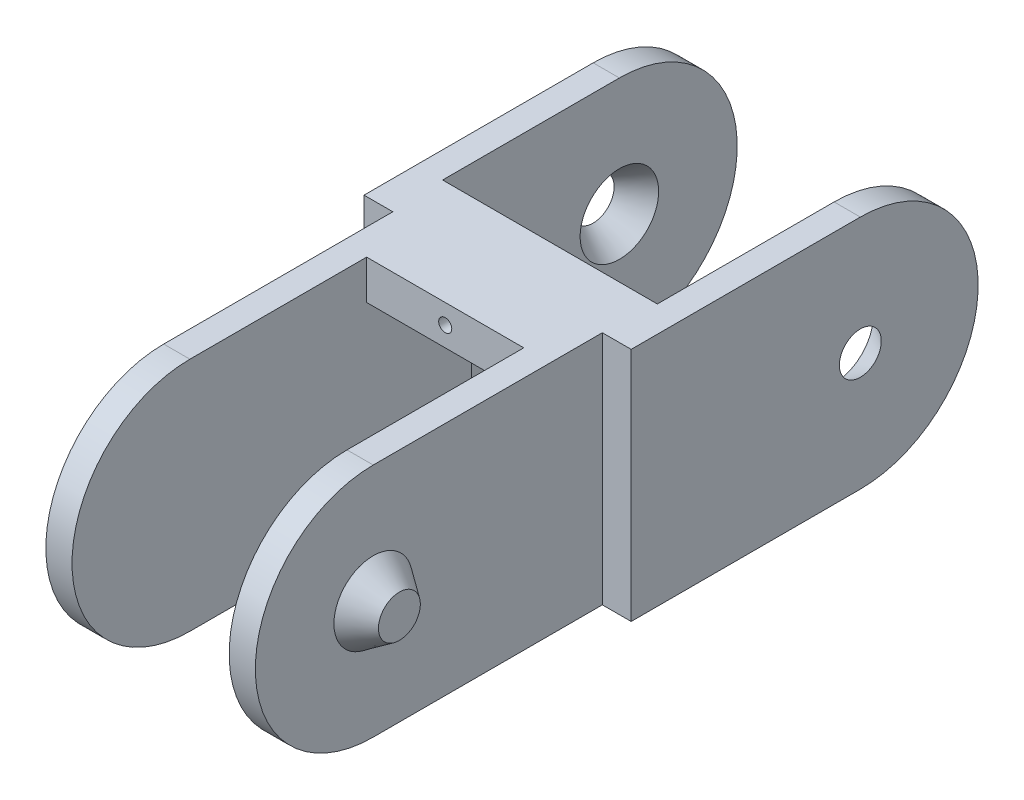
SolidWorks part; units mm, degrees
ref_plane "Front Plane" through (0, 0, 0) normal (0, 0, 1) x (1, 0, 0)
ref_plane "Top Plane" through (0, 0, 0) normal (0, 1, 0) x (1, 0, 0)
ref_plane "Right Plane" through (0, 0, 0) normal (1, 0, 0) x (0, 0, -1)
sketch "Sketch1" plane through (0, 0, 0) normal (0, 0, 1) x (1, 0, 0)
  line L1 (-6, -7) -> (6, -7)
  line L2 (-6, -7) -> (-6, 7)
  line L3 (-6, 7) -> (6, 7)
  line L4 (6, -7) -> (6, 7)
  line L5 (-6, -7) -> (6, 7) construction
  line L6 (-6, 7) -> (6, -7) construction
  point P0 (0, 0)
  dimension "D1" = 12
  dimension "D2" = 14
extrude "Extrude-Thin1" add sketch "Sketch1" along normal mid plane 8 thin
sketch "Sketch2" plane through (8, 0, 0) normal (1, 0, 0) x (0, 0, -1)
  line L0 (-4, 9) -> (4, 9) construction
  line L1 (0, 9) -> (-17.5, 9)
  line L2 (0, 9) -> (0, -9)
  line L3 (0, -9) -> (-17.5, -9)
  line L6 (-4, -9) -> (4, -9) construction
  line L7 (0, 55) -> (0, -55) construction
  line L8 (55, 0) -> (-55, 0) construction
  arc A0 (-17.5, 9) -> (-17.5, -9) centre (-17.5, 0) ccw
  dimension "D1" = 17.5
extrude "Boss-Extrude1" add sketch "Sketch2" against normal up to surface (2 mm away) up to face at (6, 0, 0)
sketch "Sketch3" plane through (8, 0, 0) normal (1, 0, 0) x (0, 0, -1)
  line L0 (55, 0) -> (-55, 0) construction
  circle A0 centre (-17.5, 0) radius 3
  arc A1 (-17.5, 9) -> (-17.5, -9) centre (-17.5, 0) ccw construction
  dimension "D1" = 6
extrude "Boss-Extrude2" add sketch "Sketch3" along normal blind 2 draft 35
sketch "Sketch4" plane through (8, 0, 0) normal (1, 0, 0) x (0, 0, -1)
  line L0 (0, 55) -> (0, -55) construction
  line L1 (0, 9) -> (17.5, 9)
  line L2 (0, 9) -> (0, -9)
  line L3 (0, -9) -> (17.5, -9)
  line L5 (-17.5, 9) -> (4, 9) construction
  line L6 (-17.5, -9) -> (4, -9) construction
  line L7 (55, 0) -> (-55, 0) construction
  arc A0 (17.5, 9) -> (17.5, -9) centre (17.5, 0) cw
  dimension "D1" = 17.5
extrude "Boss-Extrude3" add sketch "Sketch4" along normal blind 2.2
sketch "Sketch10" plane through (0, 9, 0) normal (0, 1, 0) x (1, 0, 0)
  line L1 (8, 4) -> (8.2, 4)
  line L2 (8, 4) -> (8, 29.5315)
  line L3 (8, 29.5315) -> (8.2, 29.5315)
  line L4 (8.2, 4) -> (8.2, 29.5315)
  dimension "D1" = 0.2
extrude "Cut-Extrude4" cut sketch "Sketch10" against normal up to next
sketch "Sketch5" plane through (8.2, 0, 0) normal (-1, 0, 0) x (0, 0, 1)
  circle A0 centre (-17.5, 0) radius 3
  dimension "D1" = 6
extrude "Cut-Extrude1" cut sketch "Sketch5" against normal up to next (2 mm away) draft 35
mirror "Mirror3" about plane through (0, 0, 0) normal (1, 0, 0) of "Cut-Extrude4", "Boss-Extrude1", "Cut-Extrude1", "Boss-Extrude2", "Extrude-Thin1", "Boss-Extrude3"
sketch "Sketch13" plane through (0, 0, 4) normal (0, 0, 1) x (1, 0, 0)
  line L0 (6, 9) -> (6, -9) construction
  line L1 (-6, 7) -> (6, 7)
  line L2 (-6, 7) -> (-6, 6)
  line L3 (-6, 6) -> (6, 6)
  line L4 (6, 7) -> (6, 6)
  dimension "D1" = 1
extrude "Boss-Extrude4" add sketch "Sketch13" against normal up to surface (8 mm away) up to face at (0, 0, -4)
mirror "Mirror5" about plane through (0, 0, 0) normal (0, 1, 0) of "Boss-Extrude4"
sketch "Sketch11" plane through (0, 0, 4) normal (0, 0, 1) x (1, 0, 0)
  line L0 (0, 9) -> (0, 6) construction
  line L1 (-6, 6) -> (6, 6) construction
  line L2 (6, 9) -> (-6, 9) construction
  circle A0 centre (0, 7.5) radius 0.5
  point P4 (0, 9)
  dimension "D2" = 1
extrude "Cut-Extrude5" cut sketch "Sketch11" against normal up to next
mirror "Mirror4" about plane through (0, 0, 0) normal (0, 1, 0) of "Cut-Extrude5"
